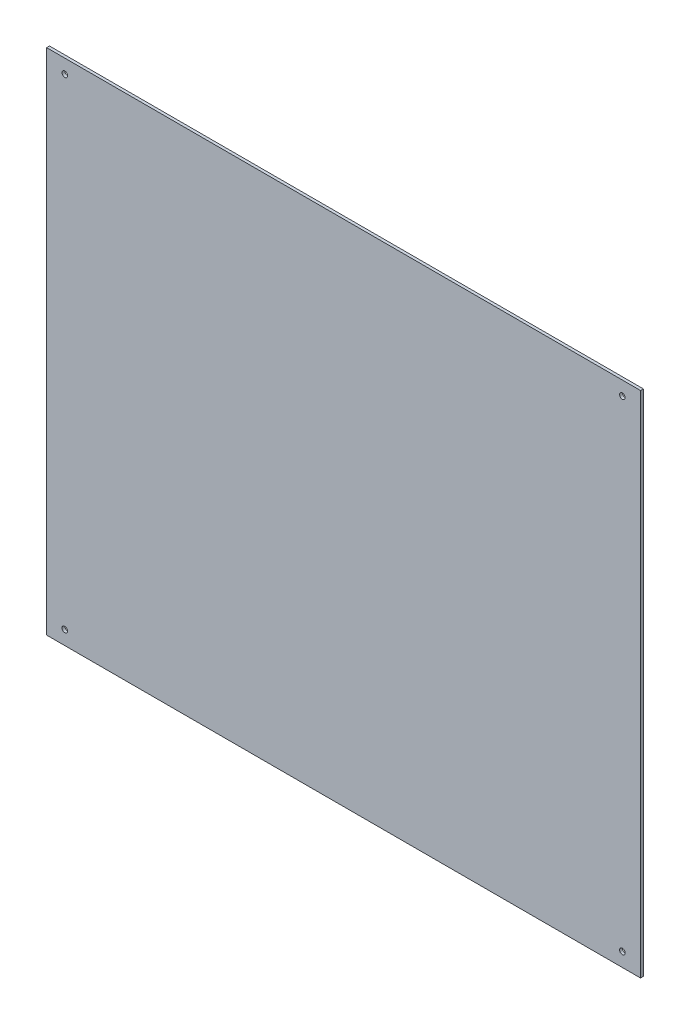
SolidWorks part; units mm, degrees
material "6061-T6 (SS)"
ref_plane "Front Plane" through (0, 0, 0) normal (0, 0, 1) x (1, 0, 0)
ref_plane "Top Plane" through (0, 0, 0) normal (0, 1, 0) x (1, 0, 0)
ref_plane "Right Plane" through (0, 0, 0) normal (1, 0, 0) x (0, 0, -1)
sketch "Sketch1" plane through (0, 0, 0) normal (0, 0, 1) x (1, 0, 0)
  line L0 (-213, 182.5) -> (213, 182.5)
  line L1 (213, 182.5) -> (213, -182.5)
  line L2 (213, -182.5) -> (-213, -182.5)
  line L3 (-213, -182.5) -> (-213, 182.5)
  line L4 (-213, 182.5) -> (213, -182.5) construction
  circle A0 centre (200, 172.5) radius 2
  circle A1 centre (-200, -172.5) radius 2
  circle A2 centre (200, -172.5) radius 2
  circle A3 centre (-200, 172.5) radius 2
  dimension "D3" = 10
  dimension "D4" = 13
  dimension "D5" = 4
  dimension "D6" = 13
  dimension "D7" = 10
  dimension "D1" = 426
  dimension "D2" = 365
extrude "Boss-Extrude1" add sketch "Sketch1" along normal blind 2.032
